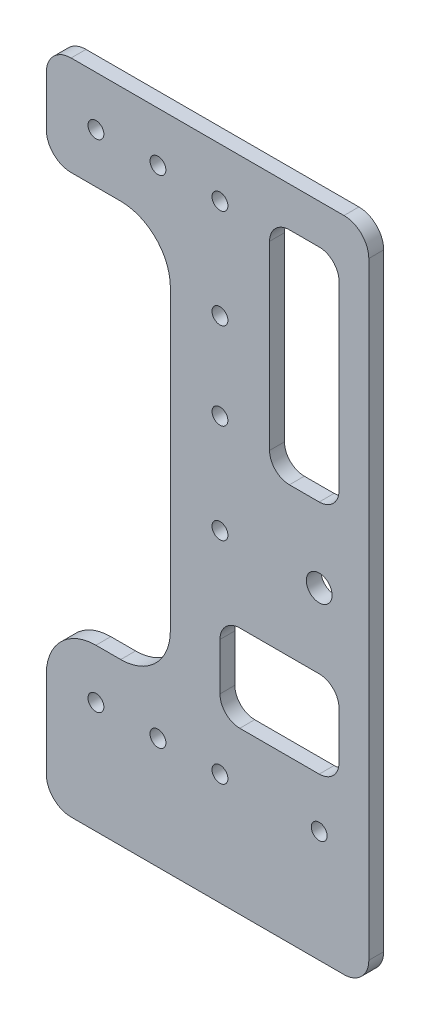
SolidWorks part; units mm, degrees
material "Thornel Mat VMA"
ref_plane "前视基准面" through (0, 0, 0) normal (0, 0, 1) x (1, 0, 0)
ref_plane "上视基准面" through (0, 0, 0) normal (0, 1, 0) x (1, 0, 0)
ref_plane "右视基准面" through (0, 0, 0) normal (1, 0, 0) x (0, 0, -1)
sketch "草图1" plane through (0, 0, 0) normal (0, 0, 1) x (1, 0, 0)
  line L0 (-60, 77.5) -> (-5, 77.5)
  line L1 (-100, 77.5) -> (-20, 77.5) construction
  line L2 (-100, 77.5) -> (-100, 57.5) construction
  line L3 (-100, 57.5) -> (-20, 57.5) construction
  line L4 (-20, 77.5) -> (-20, 57.5) construction
  line L5 (-100, 20) -> (-20, 20) construction
  line L6 (-100, 20) -> (-100, 0) construction
  line L7 (-100, 0) -> (-20, 0) construction
  line L8 (-20, 20) -> (-20, 0) construction
  line L9 (-20, 20) -> (0, 20) construction
  line L10 (-20, 20) -> (-20, 0) construction
  line L11 (-20, 0) -> (0, 0) construction
  line L12 (0, 20) -> (0, 0) construction
  line L13 (-20, 77.5) -> (-6.2325, 77.5) construction
  line L14 (-20, 77.5) -> (-20, 57.5) construction
  line L15 (-20, 57.5) -> (0, 57.5) construction
  line L16 (0, 72.5) -> (0, 57.5) construction
  line L17 (0, 72.5) -> (0, -50)
  line L18 (-5, -55) -> (-60, -55)
  line L19 (-65, -50) -> (-65, -32.5)
  line L20 (-55, -22.5) -> (-50, -22.5)
  line L21 (-40, -12.5) -> (-40, 47.5)
  line L22 (-50, 57.5) -> (-60, 57.5)
  line L23 (-65, 62.5) -> (-65, 72.5)
  line L25 (-26, -5) -> (-10, -5)
  line L26 (-30, -9) -> (-30, -18.5)
  line L27 (-26, -22.5) -> (-10, -22.5)
  line L28 (-6, -9) -> (-6, -18.5)
  line L29 (-10, 25) -> (-16, 25)
  line L30 (-6, 29) -> (-6, 65.5)
  line L31 (-10, 69.5) -> (-16, 69.5)
  line L32 (-20, 29) -> (-20, 65.5)
  circle A0 centre (-10, 10) radius 2.6
  arc A1 (-60, 57.5) -> (-65, 62.5) centre (-60, 62.5) cw
  arc A2 (-60, 77.5) -> (-65, 72.5) centre (-60, 72.5) ccw
  arc A4 (0, -50) -> (-5, -55) centre (-5, -50) cw
  arc A5 (-60, -55) -> (-65, -50) centre (-60, -50) cw
  arc A6 (-50, -22.5) -> (-40, -12.5) centre (-50, -12.5) ccw
  arc A7 (-40, 47.5) -> (-50, 57.5) centre (-50, 47.5) ccw
  arc A8 (-65, -32.5) -> (-55, -22.5) centre (-55, -32.5) cw
  circle A9 centre (-55, 67.5) radius 1.6
  circle A10 centre (-30, 10) radius 1.6
  circle A11 centre (-30, 67.5) radius 1.6
  circle A12 centre (-42.5, 67.5) radius 1.6
  circle A13 centre (-30, 47.5) radius 1.6
  circle A14 centre (-30, 30) radius 1.6
  circle A15 centre (-55, -32.5) radius 1.6
  circle A16 centre (-42.5, -32.5) radius 1.6
  circle A17 centre (-30, -32.5) radius 1.6
  circle A18 centre (-10, -32.5) radius 1.6
  arc A19 (-26, -5) -> (-30, -9) centre (-26, -9) ccw
  arc A20 (-10, -5) -> (-6, -9) centre (-10, -9) cw
  arc A21 (-10, -22.5) -> (-6, -18.5) centre (-10, -18.5) ccw
  arc A22 (-30, -18.5) -> (-26, -22.5) centre (-26, -18.5) ccw
  arc A23 (-16, 25) -> (-20, 29) centre (-16, 29) cw
  arc A24 (-10, 25) -> (-6, 29) centre (-10, 29) ccw
  arc A25 (-6, 65.5) -> (-10, 69.5) centre (-10, 65.5) ccw
  arc A26 (-16, 69.5) -> (-20, 65.5) centre (-16, 65.5) ccw
  arc A27 (-5, 77.5) -> (0, 72.5) centre (-5, 72.5) cw
  point P12 (-6.2325, 77.5)
  point P26 (-65, 57.5)
  point P29 (-65, 77.5)
  point P32 (0, 77.5)
  point P41 (-40, 57.5)
  point P87 (0, 0)
  point P90 (0, 77.5)
  dimension "D10" = 5
  dimension "D11" = 10
  dimension "D12" = 10
  dimension "D17" = 3.2
  dimension "D24" = 4
  dimension "D30" = 5.2
  dimension "D35" = 5
  dimension "D1" = 20
  dimension "D2" = 20
  dimension "D3" = 20
  dimension "D4" = 20
  dimension "D5" = 77.5
  dimension "D6" = 100
  dimension "D7" = 55
  dimension "D8" = 20
  dimension "D9" = 65
  dimension "D13" = 110
  dimension "D14" = 10
  dimension "D15" = 12.5
  dimension "D16" = 12.5
  dimension "D18" = 12.5
  dimension "D19" = 10
  dimension "D20" = 10
  dimension "D21" = 10
  dimension "D22" = 10
  dimension "D23" = 10
  dimension "D25" = 6
  dimension "D26" = 10
  dimension "D27" = 8
  dimension "D28" = 5
  dimension "D29" = 10
  dimension "D31" = 10
  dimension "D32" = 6
  dimension "D33" = 10
  dimension "D34" = 5
extrude "凸台-拉伸1" add sketch "草图1" along normal blind 3
